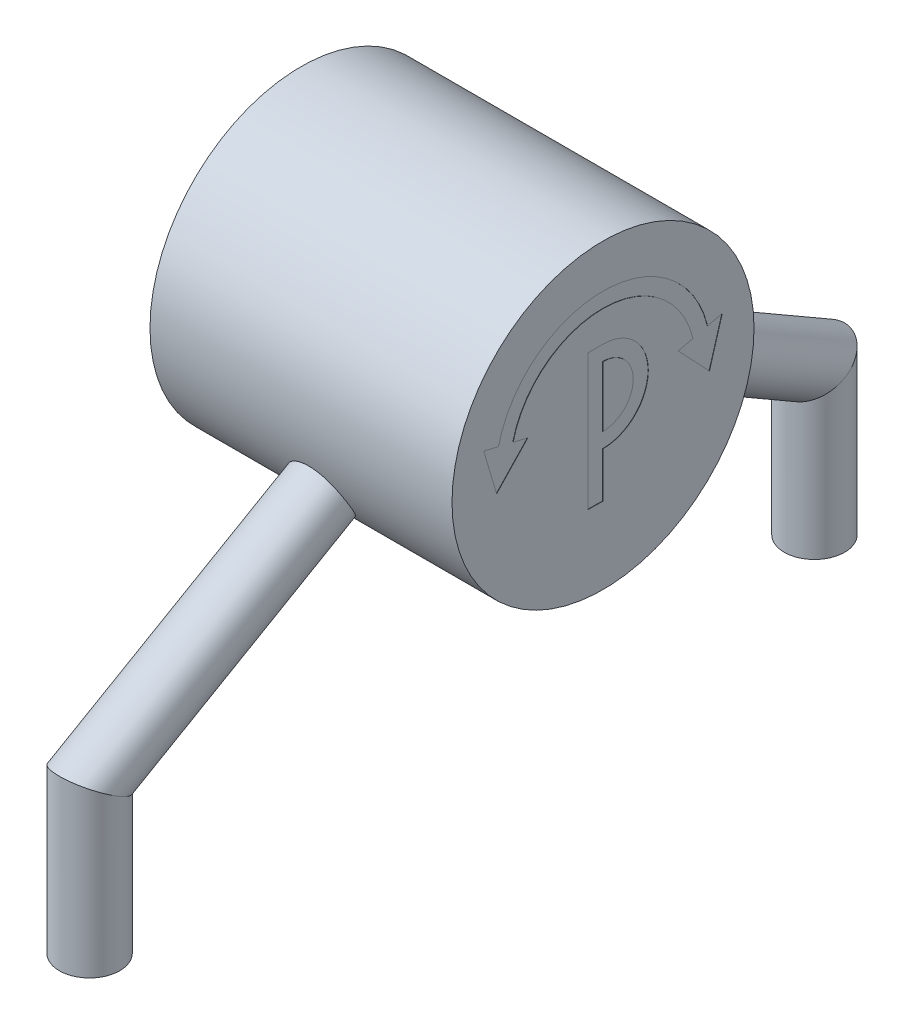
SolidWorks part; units mm, degrees
ref_plane "Front Plane" through (0, 0, 0) normal (0, 0, 1) x (1, 0, 0)
ref_plane "Top Plane" through (0, 0, 0) normal (0, 1, 0) x (1, 0, 0)
ref_plane "Right Plane" through (0, 0, 0) normal (1, 0, 0) x (0, 0, -1)
sketch "Sketch1" plane through (0, 0, 0) normal (1, 0, 0) x (0, 0, -1)
  circle A0 centre (0, 0) radius 50
  dimension "D1" = 100
extrude "Boss-Extrude1" add sketch "Sketch1" along normal mid plane 100
sketch "Sketch2" plane through (0, 0, 0) normal (1, 0, 0) x (0, 0, -1)
  line L0 (0, 0) -> (-120, -69.282)
  line L1 (-120, -69.282) -> (-120, -119.282)
  dimension "D1" = 30
  dimension "D2" = 50
  dimension "D3" = 120
sweep "Sweep1" add path "Sketch2" circular profile diameter 20 parameters "D3"=20
mirror "Mirror1" about plane through (0, 0, 0) normal (0, 0, 1) of "Sweep1"
sketch "Sketch13" plane through (50, 0, 0) normal (1, 0, 0) x (0, 0, -1)
  line L0 (-34.6313, 8.3214) -> (-39.4929, 9.4896)
  line L1 (-39.4929, 9.4896) -> (-35.2355, -4.8935)
  line L2 (-29.7696, 7.1532) -> (-24.908, 5.9851)
  line L3 (-24.908, 5.9851) -> (-35.2355, -4.8935)
  line L4 (0, 46.9892) -> (0, 20.3863) construction
  line L5 (34.6313, 8.3214) -> (39.4929, 9.4896)
  line L6 (24.908, 5.9851) -> (35.2355, -4.8935)
  line L7 (39.4929, 9.4896) -> (35.2355, -4.8935)
  line L8 (29.7696, 7.1532) -> (24.908, 5.9851)
  line L9 (-5, 20.3863) -> (-5, -24.5327)
  line L10 (0, -24.6137) -> (0, -9.6137)
  line L11 (-5, 20.3863) -> (0, 20.3863)
  line L12 (0, -9.6137) -> (0, -18.7455) construction
  line L13 (0, 15.3863) -> (0, -4.6137)
  arc A0 (-34.6313, 8.3214) -> (34.6313, 8.3214) centre (0, 0) cw
  arc A1 (-29.7696, 7.1532) -> (29.7696, 7.1532) centre (0, 0) cw
  arc A2 (-29.7696, 7.1532) -> (28.9159, 10.0633) centre (0, 0) cw construction
  arc A3 (-34.6313, 8.3214) -> (33.6381, 11.7067) centre (0, 0) cw construction
  arc A4 (-5, -24.5327) -> (0, -24.6137) centre (-5, -178.8918) cw
  arc A5 (0, 20.3863) -> (0, -9.6137) centre (0, 5.3863) cw
  arc A6 (0, 15.3863) -> (0, -4.6137) centre (0, 5.3863) cw
  point P27 (-4.9755, 21.1078)
  dimension "D1" = 5
  dimension "D4" = 15
  dimension "D5" = 15
  dimension "D8" = 199.2781
  dimension "D2" = 5
  dimension "D3" = 15
  dimension "D7" = 5
  dimension "D6" = 5
extrude "Cut-Extrude1" cut sketch "Sketch13" against normal blind 0.1
